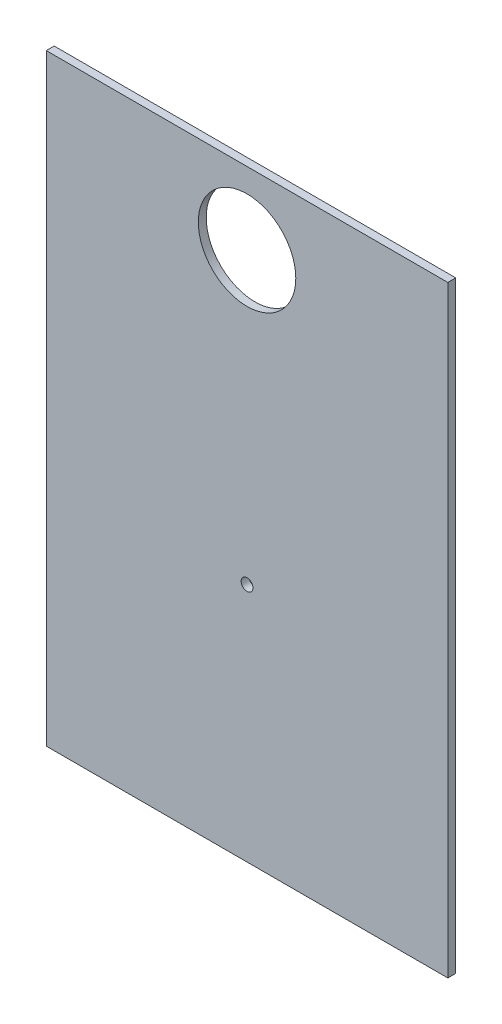
SolidWorks part; units mm, degrees
material "Acrylic (Medium-high impact)"
ref_plane "Front Plane" through (0, 0, 0) normal (0, 0, 1) x (1, 0, 0)
ref_plane "Top Plane" through (0, 0, 0) normal (0, 1, 0) x (1, 0, 0)
ref_plane "Right Plane" through (0, 0, 0) normal (1, 0, 0) x (0, 0, -1)
sketch "Sketch1" plane through (0, 0, 0) normal (0, 0, 1) x (1, 0, 0)
  line L1 (152.4, -228.6) -> (-152.4, -228.6)
  line L2 (152.4, -228.6) -> (152.4, 228.6)
  line L3 (152.4, 228.6) -> (-152.4, 228.6)
  line L4 (-152.4, -228.6) -> (-152.4, 228.6)
  line L5 (152.4, -228.6) -> (-152.4, 228.6) construction
  line L6 (152.4, 228.6) -> (-152.4, -228.6) construction
  point P0 (0, 0)
  dimension "D1" = 457.2
  dimension "D2" = 304.8
extrude "Boss-Extrude1" add sketch "Sketch1" along normal blind 6
sketch "Sketch2" plane through (0, 0, 6) normal (0, 0, 1) x (1, 0, 0)
  line L0 (-152.4, 173.6) -> (152.4, 173.6) construction
  line L1 (-152.4, 228.6) -> (-152.4, -228.6) construction
  line L2 (152.4, -228.6) -> (152.4, 228.6) construction
  line L3 (152.4, 228.6) -> (-152.4, 228.6) construction
  line L4 (-152.4, -46.2) -> (152.4, -46.2) construction
  line L5 (-152.4, -228.6) -> (152.4, -228.6) construction
  circle A0 centre (0, 173.6) radius 37
  circle A1 centre (0, -46.2) radius 4.5
  dimension "D1" = 74
  dimension "D4" = 9
  dimension "D2" = 55
  dimension "D3" = 182.4
extrude "Cut-Extrude1" cut sketch "Sketch2" against normal through all
